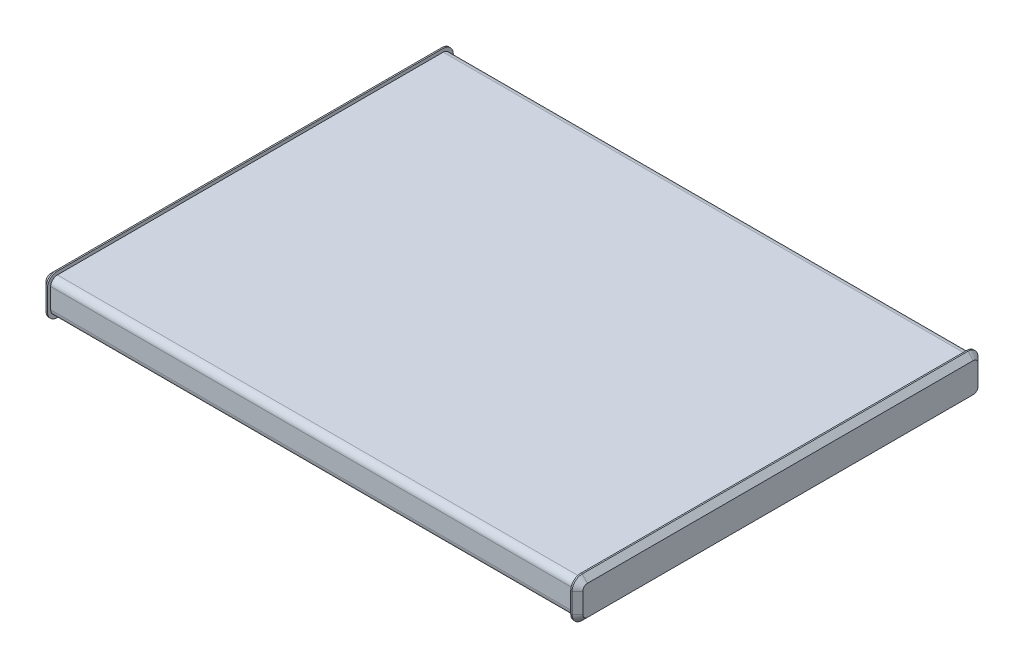
SolidWorks part; units mm, degrees
ref_plane "前视基准面" through (0, 0, 0) normal (0, 0, 1) x (1, 0, 0)
ref_plane "上视基准面" through (0, 0, 0) normal (0, 1, 0) x (1, 0, 0)
ref_plane "右视基准面" through (0, 0, 0) normal (1, 0, 0) x (0, 0, -1)
other "Configuration Table"
sketch "草图1" plane through (0, 0, 0) normal (0, 1, 0) x (1, 0, 0)
  line L1 (19.2872, 17.669) -> (99.2872, 17.669)
  line L2 (19.2872, 17.669) -> (19.2872, -41.831)
  line L3 (19.2872, -41.831) -> (99.2872, -41.831)
  line L4 (99.2872, 17.669) -> (99.2872, -41.831)
  dimension "D1" = 80
  dimension "D2" = 59.5
extrude "凸台-拉伸1" add sketch "草图1" along normal blind 5
fillet "圆角1" radius 1 4 edges at (59.2872, 0, -17.669) (59.2872, 5, -17.669) (59.2872, 0, 41.831) (59.2872, 5, 41.831)
sketch "草图2" plane through (99.2872, 0, 0) normal (1, 0, 0) x (0, 0, -1)
  line L0 (16.669, 5.5) -> (-40.831, 5.5)
  line L1 (-42.331, 4) -> (-42.331, 1)
  line L2 (-40.831, -0.5) -> (16.669, -0.5)
  line L3 (18.169, 1) -> (18.169, 4)
  line L4 (-40.831, 0) -> (16.669, 0)
  line L5 (17.669, 1) -> (17.669, 4)
  line L6 (16.669, 5) -> (-40.831, 5)
  line L7 (-41.831, 4) -> (-41.831, 1)
  line L8 (-40.831, 0) -> (16.669, 0) construction
  line L9 (17.669, 1) -> (17.669, 4) construction
  line L10 (16.669, 5) -> (-40.831, 5) construction
  line L11 (-41.831, 4) -> (-41.831, 1) construction
  arc A0 (-40.831, 5.5) -> (-42.331, 4) centre (-40.831, 4) ccw
  arc A1 (-42.331, 1) -> (-40.831, -0.5) centre (-40.831, 1) ccw
  arc A2 (16.669, -0.5) -> (18.169, 1) centre (16.669, 1) ccw
  arc A3 (18.169, 4) -> (16.669, 5.5) centre (16.669, 4) ccw
  arc A4 (16.669, 0) -> (17.669, 1) centre (16.669, 1) ccw
  arc A5 (17.669, 4) -> (16.669, 5) centre (16.669, 4) ccw
  arc A6 (-40.831, 5) -> (-41.831, 4) centre (-40.831, 4) ccw
  arc A7 (-41.831, 1) -> (-40.831, 0) centre (-40.831, 1) ccw
  arc A8 (16.669, 0) -> (17.669, 1) centre (16.669, 1) ccw construction
  arc A9 (17.669, 4) -> (16.669, 5) centre (16.669, 4) ccw construction
  arc A10 (-40.831, 5) -> (-41.831, 4) centre (-40.831, 4) ccw construction
  arc A11 (-41.831, 1) -> (-40.831, 0) centre (-40.831, 1) ccw construction
  dimension "D1" = 0
  dimension "D2" = 0.5
extrude "凸台-拉伸2" add sketch "草图2" against normal blind 1
chamfer "倒角1" distance 0.8 angle 45 8 edges at (99.2872, -0.5, 12.081) (99.2872, -0.0607, -17.7296) (99.2872, -0.0607, 41.8917) (99.2872, 2.5, -18.169) (99.2872, 2.5, 42.331) (99.2872, 5.0607, -17.7296) (99.2872, 5.0607, 41.8917) (99.2872, 5.5, 12.081)
sketch "草图3" plane through (19.2872, 0, 0) normal (-1, 0, 0) x (0, 0, 1)
  line L0 (40.831, 5.5) -> (-16.669, 5.5)
  line L1 (-18.169, 4) -> (-18.169, 1)
  line L2 (-16.669, -0.5) -> (40.831, -0.5)
  line L3 (42.331, 1) -> (42.331, 4)
  line L4 (-17.669, 4) -> (-17.669, 1)
  line L5 (-16.669, 0) -> (40.831, 0)
  line L6 (41.831, 1) -> (41.831, 4)
  line L7 (40.831, 5) -> (-16.669, 5)
  line L8 (-17.669, 4) -> (-17.669, 1) construction
  line L9 (-16.669, 0) -> (40.831, 0) construction
  line L10 (41.831, 1) -> (41.831, 4) construction
  line L11 (40.831, 5) -> (-16.669, 5) construction
  arc A0 (-16.669, 5.5) -> (-18.169, 4) centre (-16.669, 4) ccw
  arc A1 (-18.169, 1) -> (-16.669, -0.5) centre (-16.669, 1) ccw
  arc A2 (40.831, -0.5) -> (42.331, 1) centre (40.831, 1) ccw
  arc A3 (42.331, 4) -> (40.831, 5.5) centre (40.831, 4) ccw
  arc A4 (-17.669, 1) -> (-16.669, 0) centre (-16.669, 1) ccw
  arc A5 (40.831, 0) -> (41.831, 1) centre (40.831, 1) ccw
  arc A6 (41.831, 4) -> (40.831, 5) centre (40.831, 4) ccw
  arc A7 (-16.669, 5) -> (-17.669, 4) centre (-16.669, 4) ccw
  arc A8 (-17.669, 1) -> (-16.669, 0) centre (-16.669, 1) ccw construction
  arc A9 (40.831, 0) -> (41.831, 1) centre (40.831, 1) ccw construction
  arc A10 (41.831, 4) -> (40.831, 5) centre (40.831, 4) ccw construction
  arc A11 (-16.669, 5) -> (-17.669, 4) centre (-16.669, 4) ccw construction
  dimension "D1" = 0
  dimension "D2" = 0.5
extrude "凸台-拉伸3" add sketch "草图3" against normal blind 1
chamfer "倒角2" distance 0.8 angle 45 8 edges at (19.2872, -0.5, 12.081) (19.2872, -0.0607, 41.8917) (19.2872, -0.0607, -17.7296) (19.2872, 2.5, 42.331) (19.2872, 2.5, -18.169) (19.2872, 5.0607, 41.8917) (19.2872, 5.0607, -17.7296) (19.2872, 5.5, 12.081)
